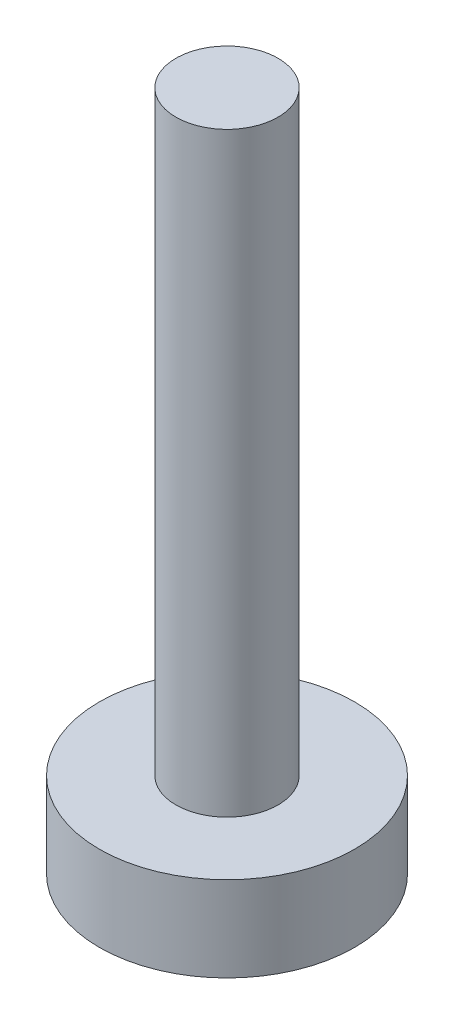
SolidWorks part; units mm, degrees
ref_plane "Front Plane" through (0, 0, 0) normal (0, 0, 1) x (1, 0, 0)
ref_plane "Top Plane" through (0, 0, 0) normal (0, 1, 0) x (1, 0, 0)
ref_plane "Right Plane" through (0, 0, 0) normal (1, 0, 0) x (0, 0, -1)
sketch "Sketch1" plane through (0, 0, 0) normal (0, 1, 0) x (1, 0, 0)
  circle A0 centre (0, 0) radius 0.6
  circle A1 centre (0, 0) radius 1.5
  dimension "D1" = 1.2
  dimension "D2" = 3
extrude "Boss-Extrude1" add sketch "Sketch1" along normal blind 7 contours A0
sketch "Sketch2" plane through (0, 0, 0) normal (0, -1, 0) x (1, 0, 0)
  circle A0 centre (0, 0) radius 1.5
  dimension "D1" = 3
extrude "Boss-Extrude2" add sketch "Sketch2" along normal blind 1
